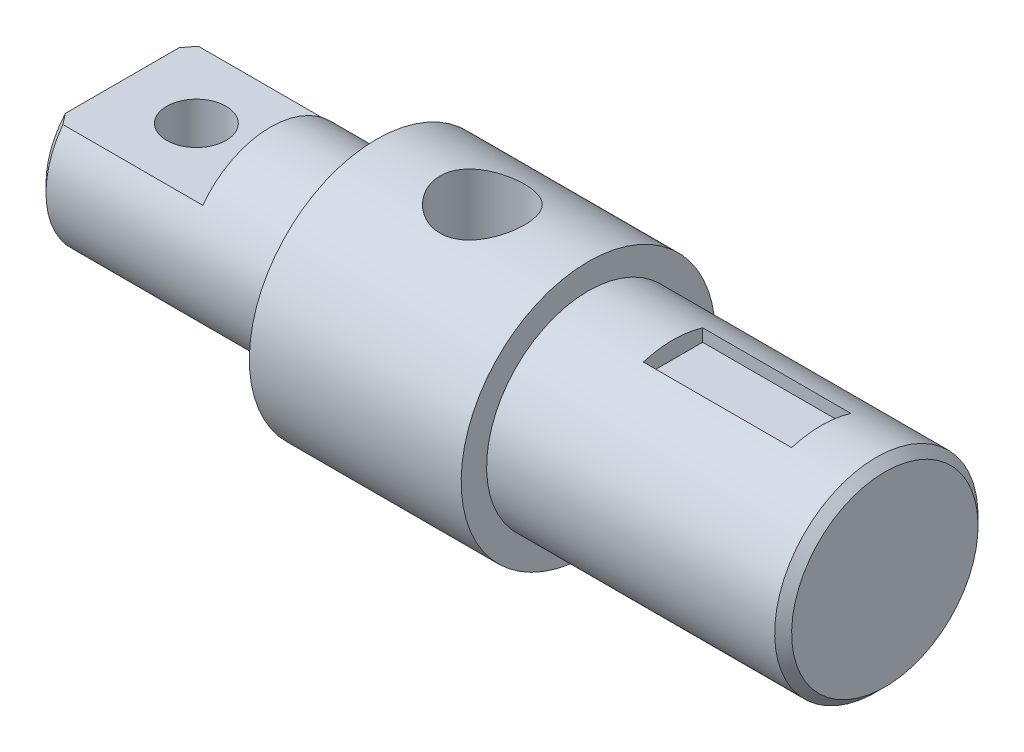
SolidWorks part; units mm, degrees
ref_plane "Спереди" through (0, 0, 0) normal (0, 0, 1) x (1, 0, 0)
ref_plane "Сверху" through (0, 0, 0) normal (0, 1, 0) x (1, 0, 0)
ref_plane "Справа" through (0, 0, 0) normal (1, 0, 0) x (0, 0, -1)
sketch "Эскиз2" plane through (0, 0, 0) normal (0, 0, 1) x (1, 0, 0)
  line L0 (180, 0) -> (0, 0) construction
  line L1 (0, 0) -> (0, 20)
  line L2 (0, 20) -> (60, 20)
  line L3 (60, 20) -> (60, 30)
  line L4 (60, 30) -> (110, 30)
  line L5 (110, 30) -> (110, 24)
  line L6 (110, 24) -> (180, 24)
  line L7 (180, 24) -> (180, 0)
  line L8 (180, 0) -> (0, 0)
  dimension "D1" = 40
  dimension "D2" = 60
  dimension "D3" = 70
  dimension "D4" = 180
  dimension "D5" = 48
  dimension "D6" = 60
revolve "Повернуть1" add sketch "Эскиз2" angle 360 about L0
sketch "Эскиз3" plane through (0, 0, 0) normal (-1, 0, 0) x (0, 0, 1)
  line L0 (-16, 12) -> (16, 12)
  circle A0 centre (0, 0) radius 20 construction
  circle A3 centre (0, 0) radius 20 construction
  arc A4 (16, 12) -> (-16, 12) centre (0, 0) ccw
  dimension "D1" = 32
extrude "Вырез-Вытянуть1" cut sketch "Эскиз3" against normal blind 35
sketch "Эскиз4" plane through (0, 0, 0) normal (0, 1, 0) x (1, 0, 0)
  line L0 (0, 0) -> (35, 0) construction
  line L1 (0, 16) -> (0, -16) construction
  line L2 (35, 16) -> (35, -16) construction
  line L3 (60, 0) -> (110, 0) construction
  line L6 (110, -24) -> (110, 24) construction
  line L7 (60, 30) -> (60, -30) construction
  circle A0 centre (17.5, 0) radius 7
  circle A1 centre (85, 0) radius 10
  point P14 (60, 0)
  point P18 (17.5, 0)
  point P21 (85, 0)
  dimension "D1" = 14
  dimension "D2" = 20
extrude "Вырез-Вытянуть2" cut sketch "Эскиз4" against normal through all both and the other way through all
ref_plane "Плоскость4" through (0, 24, 0) normal (0, 1, 0) x (1, 0, 0)
sketch "Эскиз5" plane through (0, 24, 0) normal (0, 1, 0) x (1, 0, 0)
  line L0 (180, -24) -> (180, 24) construction
  line L1 (130, -7) -> (165, -7)
  line L2 (130, -7) -> (130, 7)
  line L3 (130, 7) -> (165, 7)
  line L4 (165, -7) -> (165, 7)
  line L5 (130, -7) -> (165, 7) construction
  line L6 (130, 7) -> (165, -7) construction
  point P0 (147.5, 0)
  dimension "D1" = 35
  dimension "D2" = 14
  dimension "D3" = 15
extrude "Вырез-Вытянуть3" cut sketch "Эскиз5" against normal blind 4
chamfer "Фаска1" distance 2 angle 45 2 edges at (180, 24, 0) (0, -20, 0)
